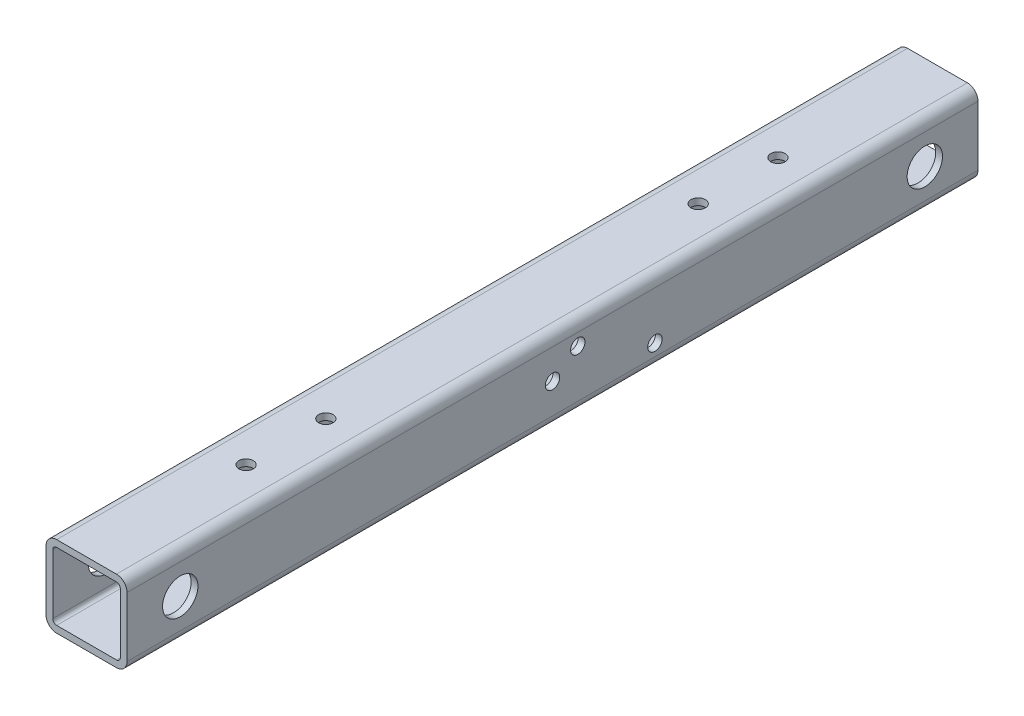
SolidWorks part; units mm, degrees
ref_plane "Front Plane" through (0, 0, 0) normal (0, 0, 1) x (1, 0, 0)
ref_plane "Top Plane" through (0, 0, 0) normal (0, 1, 0) x (1, 0, 0)
ref_plane "Right Plane" through (0, 0, 0) normal (1, 0, 0) x (0, 0, -1)
sketch "Sketch1" plane through (0, 0, 0) normal (0, 0, 1) x (1, 0, 0)
  line L6 (-14.05, 19.05) -> (14.05, 19.05)
  line L7 (19.05, 14.05) -> (19.05, -14.05)
  line L8 (-15.875, 14.05) -> (-15.875, -14.05)
  line L9 (-14.05, -15.875) -> (14.05, -15.875)
  line L10 (14.05, -19.05) -> (-14.05, -19.05)
  line L11 (-19.05, -14.05) -> (-19.05, 14.05)
  line L12 (0, 19.05) -> (0, -19.05) construction
  line L13 (-19.05, 0) -> (19.05, 0) construction
  line L14 (15.875, -14.05) -> (15.875, 14.05)
  line L15 (14.05, 15.875) -> (-14.05, 15.875)
  line L16 (0, 15.875) -> (0, -15.875) construction
  line L17 (-15.875, 0) -> (15.875, 0) construction
  arc A0 (14.05, 19.05) -> (19.05, 14.05) centre (14.05, 14.05) cw
  arc A1 (19.05, -14.05) -> (14.05, -19.05) centre (14.05, -14.05) cw
  arc A2 (-14.05, -19.05) -> (-19.05, -14.05) centre (-14.05, -14.05) cw
  arc A3 (-19.05, 14.05) -> (-14.05, 19.05) centre (-14.05, 14.05) cw
  arc A4 (-15.875, -14.05) -> (-14.05, -15.875) centre (-14.05, -14.05) ccw
  arc A5 (14.05, -15.875) -> (15.875, -14.05) centre (14.05, -14.05) ccw
  arc A6 (15.875, 14.05) -> (14.05, 15.875) centre (14.05, 14.05) ccw
  arc A7 (-14.05, 15.875) -> (-15.875, 14.05) centre (-14.05, 14.05) ccw
  point P40 (0, 0)
  dimension "D3" = 5
  dimension "D4" = 3.175
extrude "Boss-Extrude1" add sketch "Sketch1" along normal blind 400
sketch "Sketch2" plane through (0, 0, 0) normal (1, 0, 0) x (0, 0, -1)
  line L0 (-375, 0) -> (-25, 0) construction
  line L1 (20.955, 0) -> (-20.955, 0) construction
  line L2 (0, 20.955) -> (0, -20.955) construction
  circle A0 centre (-375, 0) radius 8.3125
  circle A1 centre (-25, 0) radius 8.3125
  dimension "D4" = 16.625
  dimension "D2" = 350
  dimension "D1" = 25
extrude "Cut-Extrude1" cut sketch "Sketch2" against normal through all both and the other way through all
sketch "Sketch3" plane through (0, 0, 0) normal (0, 1, 0) x (1, 0, 0)
  line L0 (0, -325) -> (0, -75) construction
  line L1 (0, -20.955) -> (0, 20.955) construction
  circle A0 centre (0, -325) radius 3.38
  circle A1 centre (0, -75) radius 3.38
  dimension "D4" = 6.76
  dimension "D2" = 250
  dimension "D3" = 75
extrude "Cut-Extrude2" cut sketch "Sketch3" along normal through all both and the other way through all
sketch "Centrepoint" plane through (0, 0, 0) normal (1, 0, 0) x (0, 0, -1)
  point P0 (-200, 0)
  dimension "D1" = 200
sketch "Sketch4" plane through (0, 0, 0) normal (1, 0, 0) x (0, 0, -1)
  line L0 (0, 20.955) -> (0, -20.955) construction
  line L1 (20.955, 0) -> (-20.955, 0) construction
  circle A0 centre (-200, 0) radius 3.38
  dimension "D1" = 6.76
  dimension "D2" = 200
extrude "Cut-Extrude3" cut sketch "Sketch4" against normal through all both and the other way through all
sketch "Sketch5" plane through (0, 0, 0) normal (1, 0, 0) x (0, 0, -1)
  line L0 (-188.1262, 8.4524) -> (-151.8738, -8.4524) construction
  line L1 (20.955, 0) -> (-20.955, 0) construction
  line L2 (0, 20.955) -> (0, -20.955) construction
  circle A0 centre (-188.1262, 8.4524) radius 3.38
  circle A1 centre (-151.8738, -8.4524) radius 3.38
  point P4 (-170, 0)
  dimension "D1" = 6.76
  dimension "D2" = 25
  dimension "D3" = 40
  dimension "D4" = 170
extrude "Cut-Extrude4" cut sketch "Sketch5" against normal through all both and the other way through all
sketch "Sketch6" plane through (0, 0, 0) normal (0, 1, 0) x (1, 0, 0)
  line L0 (0, -112.5) -> (0, -287.5) construction
  line L1 (0, -20.955) -> (0, 20.955) construction
  circle A0 centre (0, -112.5) radius 3.38
  circle A1 centre (0, -287.5) radius 3.38
  point P4 (0, -200)
  dimension "D1" = 6.76
  dimension "D2" = 175
  dimension "D3" = 200
extrude "Broom Mounting Holes" cut sketch "Sketch6" against normal through all both and the other way through all
equation "\"shovelHoleDiameter\"= 5in / 8 + 0.75"
equation "\"D4@Sketch2\"=\"shovelHoleDiameter\""
equation "\"mountHoleDiameter\"= 6.76mm"
equation "\"D4@Sketch3\"=\"mountHoleDiameter\""
equation "\"limitSwitchHoleDiameter\"= 6.76mm"
equation "\"D1@Sketch4\"=\"limitSwitchHoleDiameter\""
equation "\"bracketWidth\"= 400mm"
equation "\"mountingHoleDistance\"= 250mm"
equation "\"shovelHoleDistance\"= 350mm"
equation "\"D2@Sketch2\"=\"shovelHoleDistance\""
equation "\"D2@Sketch3\"=\"mountingHoleDistance\""
equation "\"D3@Sketch3\"=(\"bracketWidth\"-\"mountingHoleDistance\")/2"
equation "\"D2@Sketch4\"=\"bracketWidth\"/2"
equation "\"D1@Sketch5\"=\"mountHoleDiameter\""
equation "\"D4@Sketch5\"=\"bracketWidth\"/2 -30"
equation "\"D1@Sketch6\"=\"mountHoleDiameter\""
equation "\"D3@Sketch6\"=\"bracketWidth\"/2"
